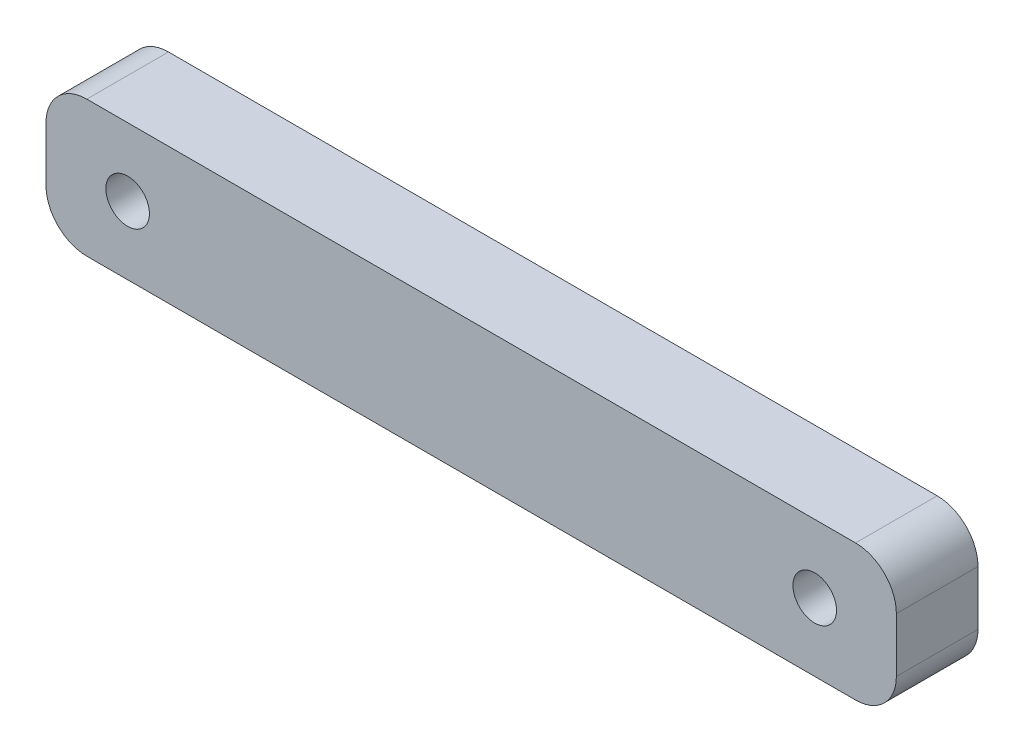
SolidWorks part; units mm, degrees
ref_plane "Front" through (0, 0, 0) normal (0, 0, 1) x (1, 0, 0)
ref_plane "Top" through (0, 0, 0) normal (0, 1, 0) x (1, 0, 0)
ref_plane "Right" through (0, 0, 0) normal (1, 0, 0) x (0, 0, -1)
sketch "Sketch1" plane through (0, 0, 0) normal (0, 0, 1) x (1, 0, 0)
  line L1 (0, 0) -> (62.5, 0)
  line L2 (0, 0) -> (0, -10)
  line L3 (0, -10) -> (62.5, -10)
  line L4 (62.5, 0) -> (62.5, -10)
  dimension "D1" = 10
  dimension "D2" = 62.5
extrude "Boss-Extrude1" add sketch "Sketch1" along normal blind 6
sketch "Sketch2" plane through (0, 0, 6) normal (0, 0, 1) x (1, 0, 0)
  line L0 (0, 0) -> (0, -10) construction
  line L1 (62.5, -10) -> (62.5, 0) construction
  circle A0 centre (56.5, -5) radius 1.6
  circle A1 centre (6, -5) radius 1.6
  dimension "D1" = 3.2
  dimension "D2" = 3.2
  dimension "D3" = 6
  dimension "D4" = 6
extrude "Cut-Extrude1" cut sketch "Sketch2" against normal through all
fillet "Fillet1" radius 3 4 edges at (62.5, -10, 3) (62.5, 0, 3) (0, -10, 3) (0, 0, 3)
